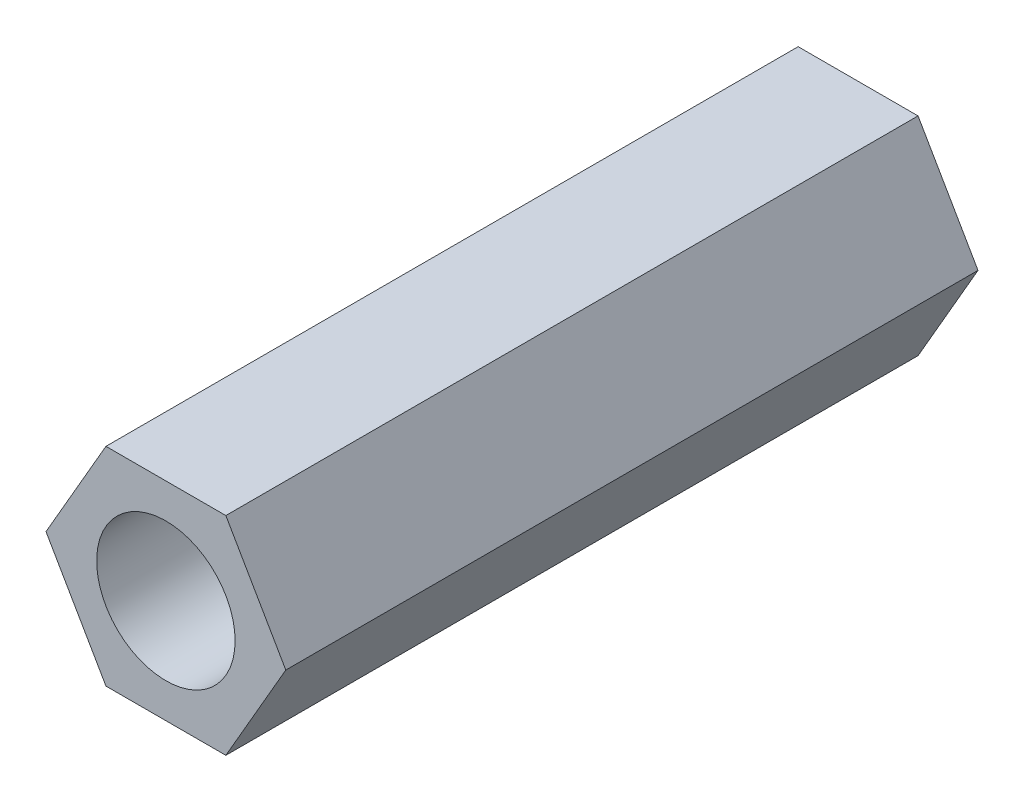
SolidWorks part; units mm, degrees
ref_plane "前视基准面" through (0, 0, 0) normal (0, 0, 1) x (1, 0, 0)
ref_plane "上视基准面" through (0, 0, 0) normal (0, 1, 0) x (1, 0, 0)
ref_plane "右视基准面" through (0, 0, 0) normal (1, 0, 0) x (0, 0, -1)
sketch "草图1" plane through (0, 0, 0) normal (0, 0, 1) x (1, 0, 0)
  line L1 (1.7321, 0) -> (0.866, 1.5)
  line L2 (0.866, 1.5) -> (-0.866, 1.5)
  line L3 (-0.866, 1.5) -> (-1.7321, 0)
  line L4 (-1.7321, 0) -> (-0.866, -1.5)
  line L5 (-0.866, -1.5) -> (0.866, -1.5)
  line L6 (0.866, -1.5) -> (1.7321, 0)
  circle A0 centre (0, 0) radius 1
  circle A1 centre (0, 0) radius 1.5 construction
  dimension "D1" = 2
  dimension "D2" = 3
extrude "凸台-拉伸1" add sketch "草图1" along normal blind 10
